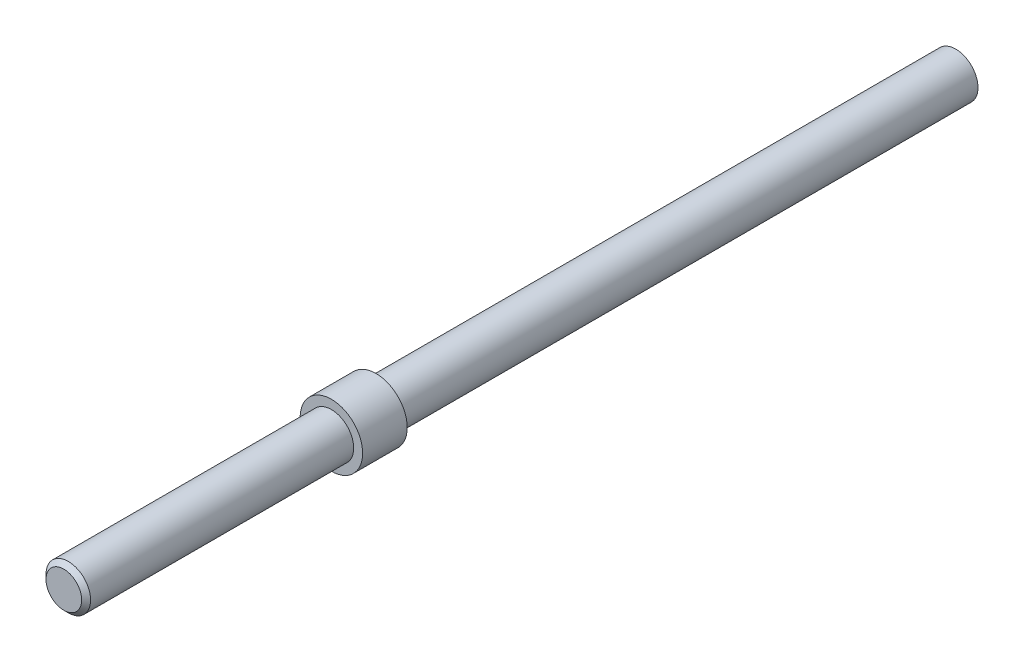
SolidWorks part; units mm, degrees
ref_plane "Front Plane" through (0, 0, 0) normal (0, 0, 1) x (1, 0, 0)
ref_plane "Top Plane" through (0, 0, 0) normal (0, 1, 0) x (1, 0, 0)
ref_plane "Right Plane" through (0, 0, 0) normal (1, 0, 0) x (0, 0, -1)
sketch "Sketch1" plane through (0, 0, 0) normal (0, 0, 1) x (1, 0, 0)
  circle A0 centre (0, 0) radius 5
  dimension "D1" = 10
extrude "Boss-Extrude1" add sketch "Sketch1" along normal blind 200
chamfer "Chamfer1" distance 1 angle 45 1 edges at (5, 0, 200)
ref_plane "Plane1" through (0, 0, 135) normal (0, 0, 1) x (1, 0, 0)
sketch "Sketch2" plane through (0, 0, 135) normal (0, 0, 1) x (1, 0, 0)
  circle A0 centre (0, 0) radius 7
  dimension "D1" = 14
extrude "Boss-Extrude2" add sketch "Sketch2" along normal mid plane 10
